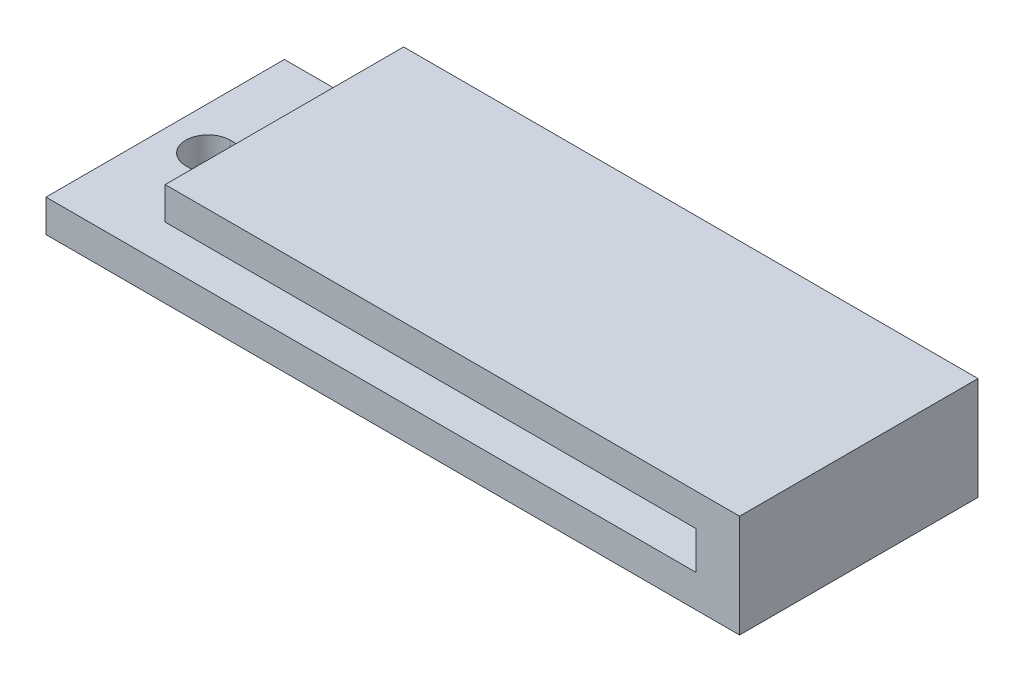
SolidWorks part; units mm, degrees
ref_plane "Front Plane" through (0, 0, 0) normal (0, 0, 1) x (1, 0, 0)
ref_plane "Top Plane" through (0, 0, 0) normal (0, 1, 0) x (1, 0, 0)
ref_plane "Right Plane" through (0, 0, 0) normal (1, 0, 0) x (0, 0, -1)
sketch "Sketch1" plane through (0, 0, 0) normal (0, 1, 0) x (1, 0, 0)
  line L0 (0, 0) -> (0, 22)
  line L1 (0, 22) -> (-49, 22)
  line L2 (-49, 22) -> (-49, 0)
  line L3 (-49, 0) -> (0, 0)
  dimension "D1" = 22
  dimension "D2" = 49
extrude "Boss-Extrude1" add sketch "Sketch1" along normal blind 3
sketch "Sketch2" plane through (0, 0, 0) normal (0, 0, 1) x (1, 0, 0)
  line L0 (0, 0) -> (0, -3.5)
  line L1 (0, -3.5) -> (4, -3.5)
  line L2 (0, 0) -> (0, 3)
  line L3 (0, 3) -> (4, 3)
  line L4 (4, 3) -> (4, -3.5)
  dimension "D1" = 3.5
  dimension "D2" = 4
extrude "Boss-Extrude2" add sketch "Sketch2" against normal up to vertex (22 mm away)
sketch "Sketch3" plane through (0, -3.5, 0) normal (0, -1, 0) x (1, 0, 0)
  line L0 (0, 0) -> (-60, 0)
  line L1 (0, -22) -> (-60, -22)
  line L2 (-60, -22) -> (-60, 0)
  line L3 (0, 0) -> (4, 0)
  line L4 (4, 0) -> (4, -22)
  line L5 (4, -22) -> (0, -22)
  dimension "D1" = 60
extrude "Boss-Extrude3" add sketch "Sketch3" along normal blind 3
sketch "Sketch4" plane through (0, -6.5, 0) normal (0, -1, 0) x (1, 0, 0)
  line L0 (4, -11) -> (-54, -11) construction
  line L1 (4, -22) -> (4, 0) construction
  line L2 (-54, -11) -> (-56.05, -11) construction
  line L3 (-56.05, -11) -> (-56.05, -8.95) construction
  line L4 (-54, -11) -> (-54, -8.95) construction
  line L5 (-56.05, -8.95) -> (-54, -8.95)
  line L6 (-54, -11) -> (-54, -13.05) construction
  line L7 (-56.05, -11) -> (-56.05, -13.05) construction
  line L8 (-56.05, -13.05) -> (-54, -13.05)
  circle A0 centre (-54, -11) radius 2.05 construction
  circle A1 centre (-56.05, -11) radius 2.05 construction
  arc A2 (-54, -8.95) -> (-54, -13.05) centre (-54, -11) cw
  arc A3 (-56.05, -8.95) -> (-56.05, -13.05) centre (-56.05, -11) ccw
  dimension "D2" = 4.1
  dimension "D3" = 4.1
  dimension "D1" = 58
  dimension "D4" = 2.05
extrude "Cut-Extrude1" cut sketch "Sketch4" against normal blind 3
